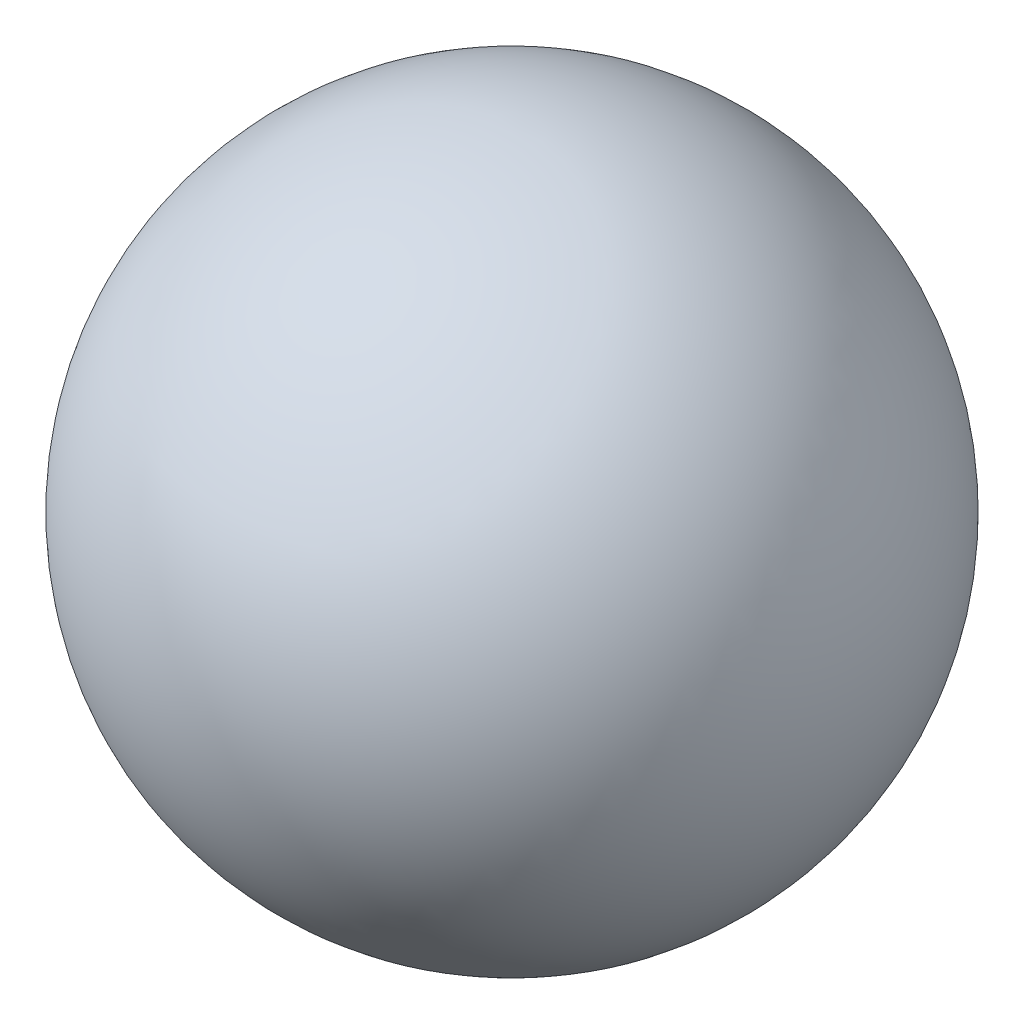
SolidWorks part; units mm, degrees
material "Rubber"
ref_plane "Front Plane" through (0, 0, 0) normal (0, 0, 1) x (1, 0, 0)
ref_plane "Top Plane" through (0, 0, 0) normal (0, 1, 0) x (1, 0, 0)
ref_plane "Right Plane" through (0, 0, 0) normal (1, 0, 0) x (0, 0, -1)
sketch "Sketch1" plane through (0, 0, 0) normal (0, 0, 1) x (1, 0, 0)
  line L0 (0, -33.5) -> (0, 33.5) construction
  line L1 (0, 33.5) -> (0, -33.5)
  arc A0 (0, 33.5) -> (0, -33.5) centre (0, 0) ccw
  dimension "D1" = 67
revolve "Revolve3" add sketch "Sketch1" angle 360 about L0
sketch3d "3DSketch2"
  point P0 (17.6825, -26.7858, -9.5969)
ref_plane "Plane2" through (0, -26.7858, 0) normal (0, -1, 0) x (-1, 0, 0)
sketch "Sketch2" plane through (0, -26.7858, 0) normal (0, -1, 0) x (-1, 0, 0)
  circle A0 centre (0, 0) radius 1.5
  dimension "D1" = 3
